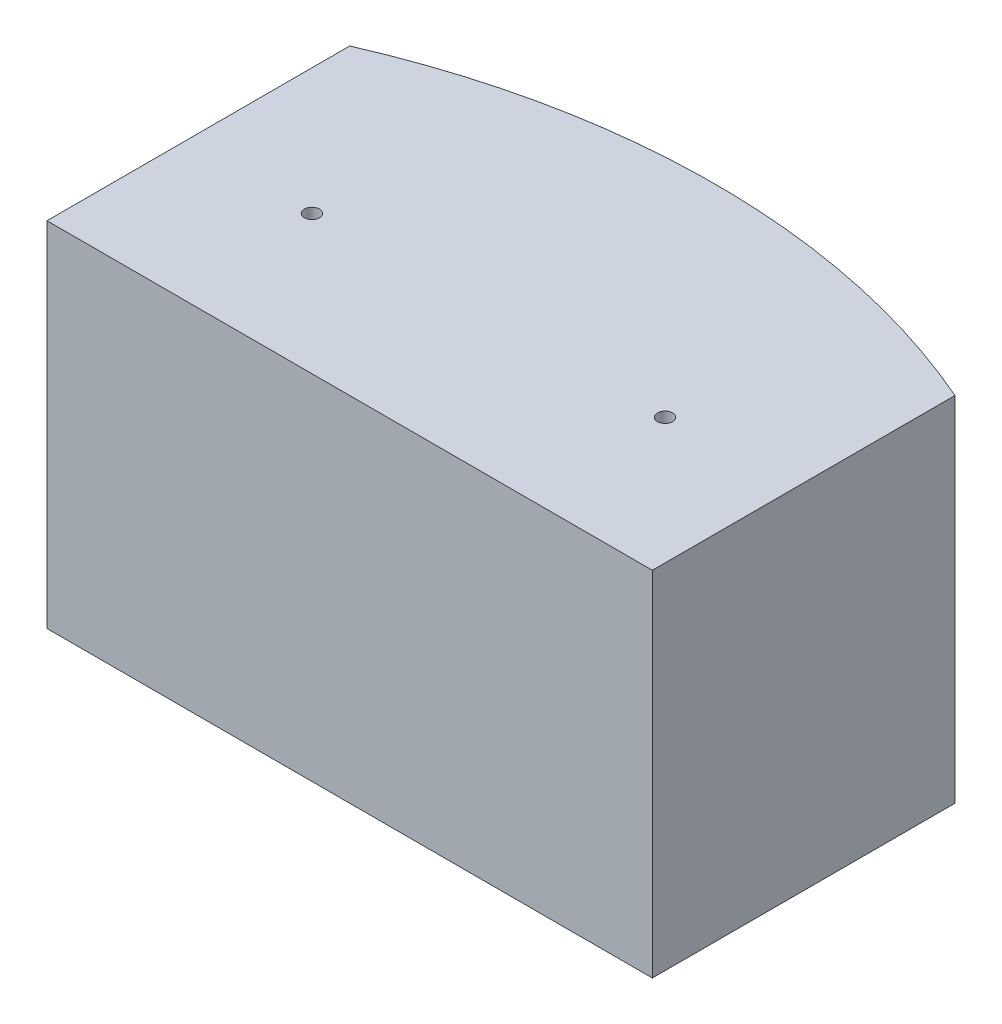
SolidWorks part; units mm, degrees
ref_plane "Front Plane" through (0, 0, 0) normal (0, 0, 1) x (1, 0, 0)
ref_plane "Top Plane" through (0, 0, 0) normal (0, 1, 0) x (1, 0, 0)
ref_plane "Right Plane" through (0, 0, 0) normal (1, 0, 0) x (0, 0, -1)
sketch "Sketch1" plane through (0, 0, 0) normal (0, 1, 0) x (1, 0, 0)
  line L0 (0, 0) -> (0, 150) construction
  line L2 (-60, 137.4773) -> (-60, 77.4773)
  line L3 (-60, 77.4773) -> (60, 77.4773)
  line L4 (60, 137.4773) -> (60, 77.4773)
  line L5 (-60, 105) -> (60, 105) construction
  arc A0 (60, 137.4773) -> (-60, 137.4773) centre (0, 0) ccw
  dimension "D1" = 300
  dimension "D2" = 120
  dimension "D3" = 45
  dimension "D4" = 60
extrude "Boss-Extrude1" add sketch "Sketch1" along normal blind 70
sketch "Sketch7" plane through (0, 0, -77.4773) normal (0, 0, 1) x (1, 0, 0)
  line L8 (-57, 3) -> (57, 3)
  line L9 (57, 3) -> (57, 67)
  line L10 (57, 67) -> (-57, 67)
  line L11 (-57, 67) -> (-57, 3)
  line L12 (-57, 3) -> (57, 3)
  line L13 (57, 3) -> (57, 67)
  line L14 (57, 67) -> (-57, 67)
  line L15 (-57, 67) -> (-57, 3)
  dimension "D1" = 3
extrude "Cut-Extrude2" cut sketch "Sketch7" against normal blind 77
sketch "Sketch8" plane through (-57, 0, 0) normal (1, 0, 0) x (0, 0, -1)
  line L0 (138.748, 67) -> (77.4773, 67) construction
  line L1 (77.4773, 3) -> (80.4773, 3)
  line L2 (77.4773, 3) -> (77.4773, 67)
  line L3 (77.4773, 67) -> (80.4773, 67)
  line L4 (80.4773, 3) -> (80.4773, 67)
  dimension "D1" = 3
extrude "Boss-Extrude3" add sketch "Sketch8" along normal up to surface (114 mm away) up to face at (57, 35, -108.1126)
sketch "Sketch9" plane through (0, 0, -80.4773) normal (0, 0, -1) x (-1, 0, 0)
  line L0 (-57, 35) -> (57, 35) construction
  line L1 (-57, 3) -> (-57, 67) construction
  line L2 (57, 3) -> (57, 67) construction
  line L3 (-57, 36.5) -> (57, 36.5)
  line L4 (-57, 33.5) -> (57, 33.5)
  line L5 (57, 67) -> (57, 3) construction
  line L6 (-57, 33.5) -> (-57, 36.5)
  line L7 (57, 36.5) -> (57, 33.5)
  dimension "D1" = 1.5
extrude "Boss-Extrude4" add sketch "Sketch9" along normal up to surface (58.2707 mm away)
sketch "Sketch10" plane through (0, 70, 0) normal (0, 1, 0) x (1, 0, 0)
  line L0 (-60, 104.9973) -> (60, 104.9973) construction
  line L1 (-60, 137.4773) -> (-60, 77.4773) construction
  line L2 (60, 77.4773) -> (60, 137.4773) construction
  line L3 (-60, 77.4773) -> (60, 77.4773) construction
  line L4 (0, 77.4773) -> (0, 104.9973) construction
  circle A0 centre (-35, 104.9973) radius 1.5
  circle A1 centre (35, 104.9973) radius 1.5
  dimension "D2" = 3
  dimension "D3" = 3
  dimension "D1" = 27.52
  dimension "D4" = 35
extrude "Cut-Extrude3" cut sketch "Sketch10" against normal up to surface (3 mm away) up to face at (0, 67, -112.4256)
